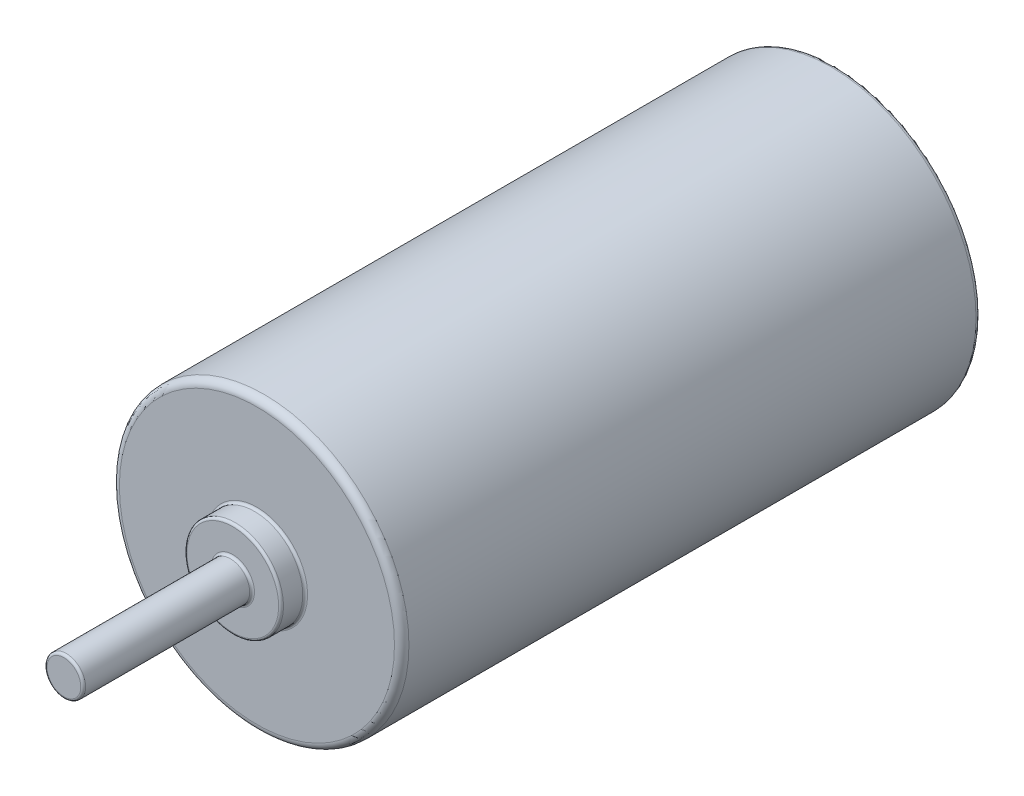
SolidWorks part; units mm, degrees
ref_plane "Front Plane" through (0, 0, 0) normal (0, 0, 1) x (1, 0, 0)
ref_plane "Top Plane" through (0, 0, 0) normal (0, 1, 0) x (1, 0, 0)
ref_plane "Right Plane" through (0, 0, 0) normal (1, 0, 0) x (0, 0, -1)
sketch "Sketch1" plane through (0, 0, 0) normal (1, 0, 0) x (0, 0, -1)
  line L0 (-94.8303, 0) -> (125.22, 0) construction
  line L1 (0, 3) -> (12, 3)
  line L2 (0, 4.4) -> (0, -4.4) construction
  line L3 (12, 3) -> (12, 0)
  line L4 (0, 3) -> (0, 1)
  line L5 (0, 1) -> (-0.5, 1)
  line L6 (-0.5, 1) -> (-0.5, 0.4)
  line L7 (-0.5, 0.4) -> (-4, 0.4)
  line L8 (-4, 0.4) -> (-4, 0)
  line L9 (12, 0) -> (-4, 0)
  dimension "D1" = 6
  dimension "D2" = 12
  dimension "D3" = 12.5
  dimension "D4" = 2
  dimension "D5" = 0.8
  dimension "D6" = 16
revolve "Revolve1" add sketch "Sketch1" angle 360 about L0
fillet "Fillet1" radius 0.05 4 edges at (0.4, 0, 4) (0.4, 0, 0.5) (1, 0, 0) (1, 0, 0.5)
fillet "Fillet3" radius 0.15 1 edges at (3, 0, 0)
fillet "Fillet4" radius 0.1 1 edges at (3, 0, -12)
